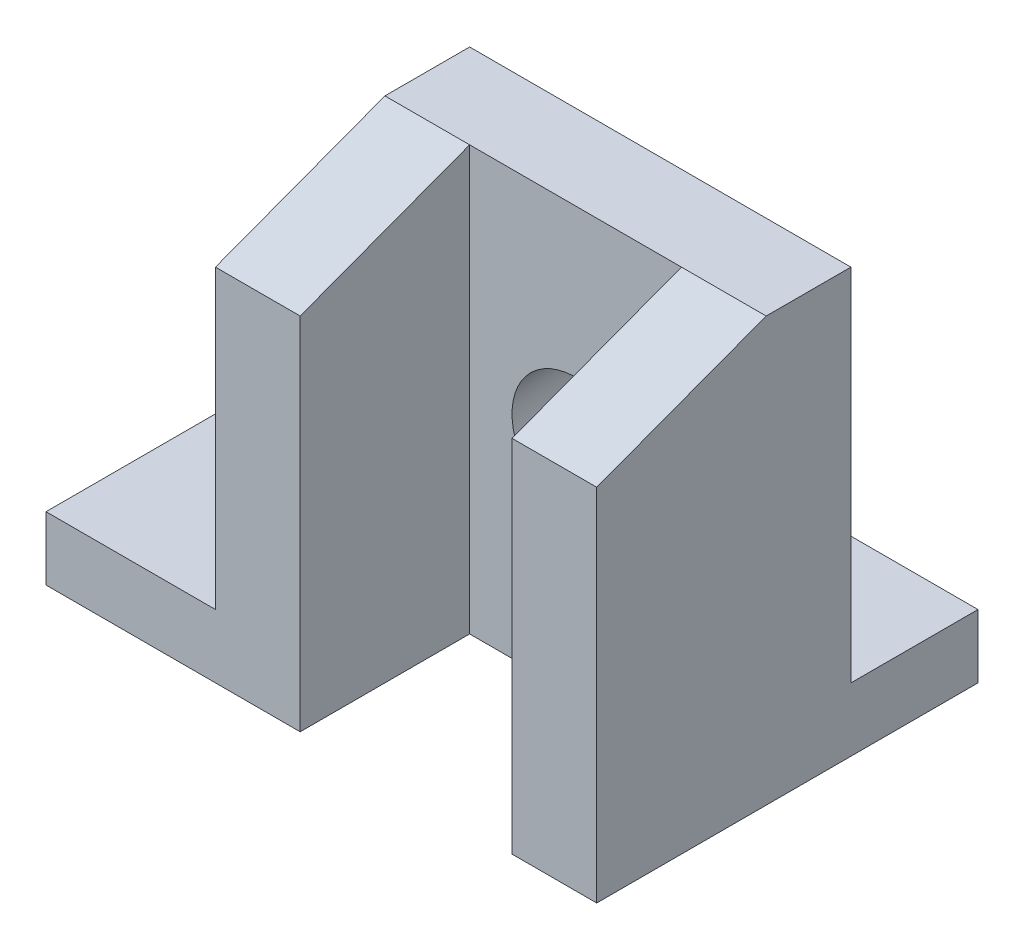
SolidWorks part; units mm, degrees
ref_plane "Front Plane" through (0, 0, 0) normal (0, 0, 1) x (1, 0, 0)
ref_plane "Top Plane" through (0, 0, 0) normal (0, 1, 0) x (1, 0, 0)
ref_plane "Right Plane" through (0, 0, 0) normal (1, 0, 0) x (0, 0, -1)
sketch "Sketch1" plane through (0, 0, 0) normal (0, 0, 1) x (1, 0, 0)
  line L0 (0, 41.2907) -> (0, -41.2907) construction
  line L1 (-18, -20) -> (18, -20)
  line L2 (-18, -20) -> (-18, 20)
  line L3 (-18, 20) -> (18, 20)
  line L4 (18, -20) -> (18, 20)
  circle A0 centre (0, 0) radius 6
  point P7 (0, 0)
  point P10 (0, 0)
  dimension "D1" = 12
  dimension "D2" = 20
  dimension "D3" = 36
  dimension "D4" = 40
extrude "Boss-Extrude1" add sketch "Sketch1" against normal blind 8
sketch "Sketch2" plane through (0, 0, 0) normal (1, 0, 0) x (0, 0, -1)
  line L0 (0, 20) -> (-16, 14)
  line L1 (-16, 14) -> (-16, -20)
  line L2 (-16, -20) -> (0, -20)
  line L3 (0, 20) -> (0, -20)
  dimension "D1" = 6
  dimension "D2" = 24
extrude "Boss-Extrude2" add sketch "Sketch2" along normal through all from offset 10
mirror "Mirror1" about plane through (0, 0, 0) normal (1, 0, 0) of "Boss-Extrude2"
sketch "Sketch3" plane through (-18, 0, 0) normal (-1, 0, 0) x (0, 0, 1)
  line L0 (-8, -20) -> (16, -20) construction
  line L1 (4, 8) -> (12, 8)
  line L2 (4, 8) -> (4, -8)
  line L3 (4, -8) -> (12, -8)
  line L4 (12, 8) -> (12, -8)
  line L5 (16, 14) -> (16, -20) construction
  dimension "D1" = 16
  dimension "D2" = 12
  dimension "D3" = 8
  dimension "D4" = 4
extrude "Boss-Extrude3" add sketch "Sketch3" along normal blind 4
ref_plane "Plane1" through (-34, 0, 0) normal (1, 0, 0) x (0, 0, -1)
sketch "Sketch5" plane through (-34, 0, 0) normal (1, 0, 0) x (0, 0, -1)
  line L1 (-16, -20) -> (20, -20)
  line L2 (-16, -20) -> (-16, -14)
  line L3 (-16, -14) -> (20, -14)
  line L4 (20, -20) -> (20, -14)
  dimension "D1" = 6
  dimension "D2" = 36
extrude "Boss-Extrude4" add sketch "Sketch5" along direction (-1, 0, 0) on the side of the normal up to surface (16 mm away)
sketch "Sketch7" plane through (-18, 0, 0) normal (1, 0, 0) x (0, 0, -1)
  line L1 (8, -14) -> (20, -14)
  line L2 (8, -14) -> (8, -20)
  line L3 (8, -20) -> (20, -20)
  line L4 (20, -14) -> (20, -20)
extrude "Boss-Extrude5" add sketch "Sketch7" along normal through all
